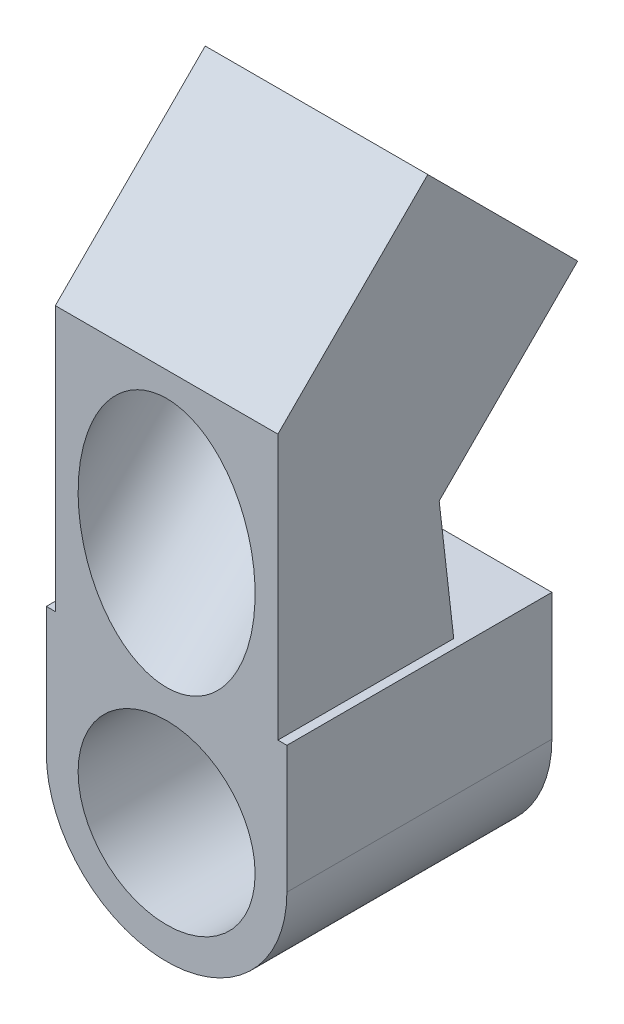
SolidWorks part; units mm, degrees
ref_plane "Alzado" through (0, 0, 0) normal (0, 0, 1) x (1, 0, 0)
ref_plane "Planta" through (0, 0, 0) normal (0, 1, 0) x (1, 0, 0)
ref_plane "Vista lateral" through (0, 0, 0) normal (1, 0, 0) x (0, 0, -1)
sketch "Croquis1" plane through (0, 0, 0) normal (0, 0, 1) x (1, 0, 0)
  line L0 (0, 0) -> (0, -10) construction
  line L4 (0, 0) -> (0, 12) construction
  line L5 (-11.35, 12) -> (11.35, 12)
  line L6 (-11.35, 12) -> (-11.35, 0)
  line L7 (11.35, 12) -> (11.35, 0)
  circle A0 centre (0, 0) radius 8.35
  arc A2 (-11.35, 0) -> (11.35, 0) centre (0, 0) ccw
  point P8 (0, -10)
  point P9 (0, 12)
  dimension "D1" = 16.7
  dimension "D2" = 3
  dimension "D4" = 12
extrude "Saliente-Extruir1" add sketch "Croquis1" against normal mid plane 25
sketch "Croquis2" plane through (0, 0, 0) normal (1, 0, 0) x (0, 0, -1)
  line L0 (-12.5, 12) -> (-12.5, 37)
  line L1 (-12.5, 37) -> (1.6421, 51.1421)
  line L2 (1.6421, 51.1421) -> (15.7843, 37)
  line L3 (12.5, 12) -> (-12.5, 12) construction
  line L4 (-12.5, 12) -> (4.0901, 12)
  line L5 (15.7843, 37) -> (2.7167, 23.9324)
  line L6 (2.7167, 23.9324) -> (4.0901, 12)
  dimension "D4" = 135
  dimension "D1" = 25
  dimension "D2" = 20
  dimension "D3" = 20
extrude "Saliente-Extruir2" add sketch "Croquis2" along normal mid plane 21
ref_plane "Plano1" through (0, 26.3921, -26.3921) normal (0, 0.7071, -0.7071) x (-1, 0, 0)
sketch "Croquis3" plane through (0, 26.3921, -26.3921) normal (0, 0.7071, -0.7071) x (1, 0, 0)
  line L0 (0, -35.0018) -> (0, -15.0018) construction
  line L1 (10.5, -35.0018) -> (-10.5, -35.0018) construction
  line L4 (10.5, -15.0018) -> (-10.5, -15.0018) construction
  circle A0 centre (0, -25.0018) radius 8.35
  point P4 (0, 0)
  point P10 (0, 0)
  dimension "D1" = 16.7
extrude "Cortar-Extruir1" cut sketch "Croquis3" against normal blind 47
